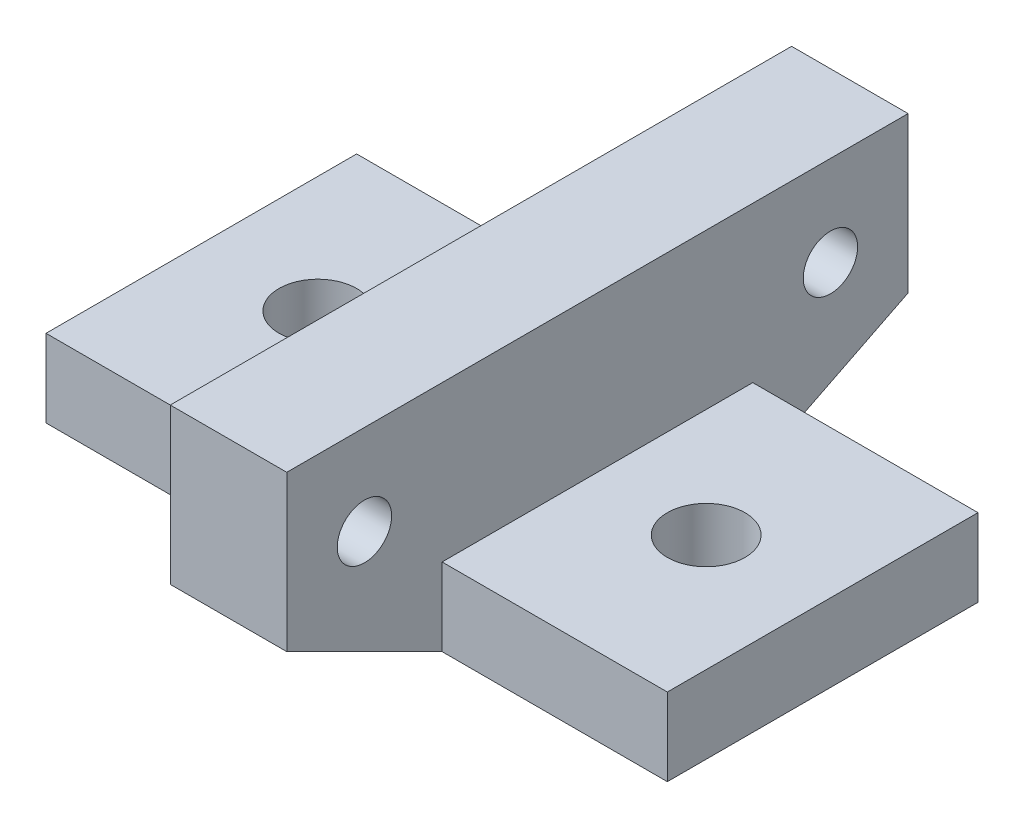
SolidWorks part; units mm, degrees
ref_plane "前视基准面" through (0, 0, 0) normal (0, 0, 1) x (1, 0, 0)
ref_plane "上视基准面" through (0, 0, 0) normal (0, 1, 0) x (1, 0, 0)
ref_plane "右视基准面" through (0, 0, 0) normal (1, 0, 0) x (0, 0, -1)
sketch "草图1" plane through (0, 0, 0) normal (0, 1, 0) x (1, 0, 0)
  line L0 (0, 0) -> (0, 10) construction
  line L1 (-20, 10) -> (20, 10)
  line L2 (-20, 10) -> (-20, -10)
  line L3 (-20, -10) -> (20, -10)
  line L4 (20, 10) -> (20, -10)
  line L5 (-20, 10) -> (20, -10) construction
  line L6 (-20, -10) -> (20, 10) construction
  circle A0 centre (-12.5, 0) radius 2.5
  circle A1 centre (12.5, 0) radius 2.5
  point P0 (0, 0)
  dimension "D3" = 5
  dimension "D1" = 20
  dimension "D2" = 40
  dimension "D4" = 25
extrude "凸台-拉伸1" add sketch "草图1" along normal blind 5
sketch "草图2" plane through (0, 5, 0) normal (0, 1, 0) x (1, 0, 0)
  line L0 (-20, 10) -> (-20, -10) construction
  line L1 (-2, 20) -> (5.5, 20)
  line L2 (-2, 20) -> (-2, -20)
  line L3 (-2, -20) -> (5.5, -20)
  line L4 (5.5, 20) -> (5.5, -20)
  line L5 (-2, 20) -> (5.5, -20) construction
  line L6 (-2, -20) -> (5.5, 20) construction
  line L7 (20, 10) -> (-20, 10) construction
  line L8 (0, 10) -> (0, -10) construction
  line L9 (-20, -10) -> (20, -10) construction
  point P0 (1.75, 0)
  point P8 (-20, 0)
  point P16 (0, 0)
  dimension "D1" = 7.5
  dimension "D2" = 40
  dimension "D3" = 2
extrude "凸台-拉伸2" add sketch "草图2" along normal blind 10
sketch "草图3" plane through (5.5, 0, 0) normal (1, 0, 0) x (0, 0, -1)
  line L0 (0, 15) -> (0, 5) construction
  line L1 (-20, 15) -> (20, 15) construction
  line L2 (-10, 5) -> (10, 5) construction
  line L3 (-20, 5) -> (-10, 5) construction
  circle A0 centre (-15, 9.2) radius 1.75
  circle A1 centre (15, 9.2) radius 1.75
  dimension "D1" = 3.5
  dimension "D2" = 30
  dimension "D3" = 4.2
extrude "切除-拉伸1" cut sketch "草图3" against normal blind 10
sketch "草图4" plane through (5.5, 0, 0) normal (1, 0, 0) x (0, 0, -1)
  line L0 (-20, 5) -> (-10, 0)
  line L1 (-10, 0) -> (-10, 5)
  line L2 (-10, 5) -> (-20, 5)
  line L3 (10, 5) -> (10, 0)
  line L4 (10, 0) -> (20, 5)
  line L5 (20, 5) -> (10, 5)
extrude "凸台-拉伸3" add sketch "草图4" against normal up to surface (7.5 mm away) up to face at (-2, 9.2, 13.25)
